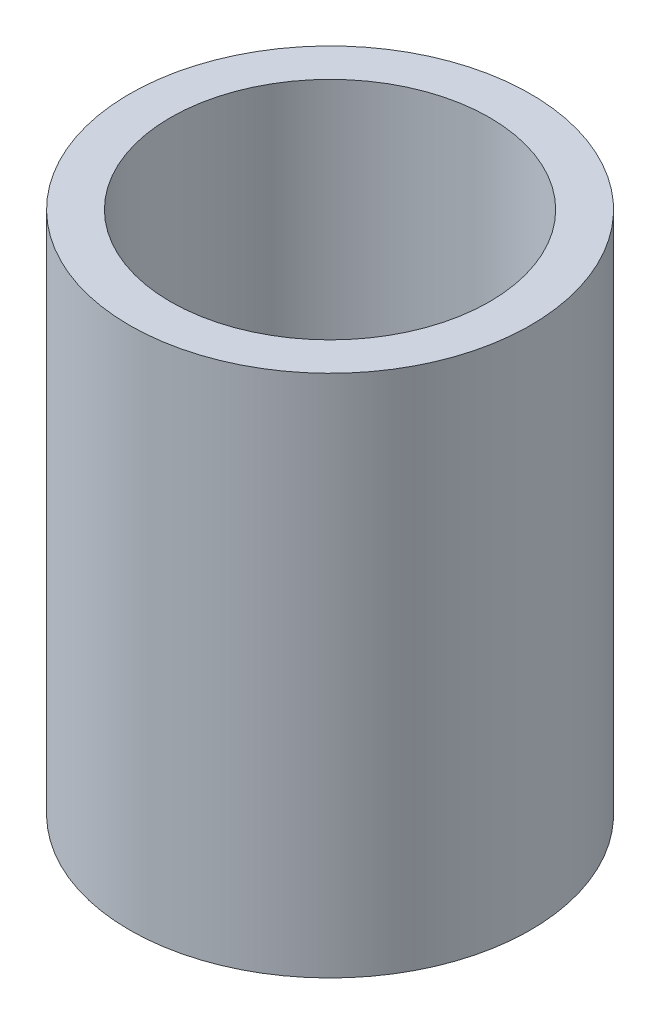
SolidWorks part; units mm, degrees
ref_plane "Front Plane" through (0, 0, 0) normal (0, 0, 1) x (1, 0, 0)
ref_plane "Top Plane" through (0, 0, 0) normal (0, 1, 0) x (1, 0, 0)
ref_plane "Right Plane" through (0, 0, 0) normal (1, 0, 0) x (0, 0, -1)
sketch "Sketch1" plane through (0, 0, 0) normal (0, 1, 0) x (1, 0, 0)
  circle A0 centre (0, 0) radius 24.5
  circle A1 centre (0, 0) radius 19.5
  dimension "D1" = 49
  dimension "D2" = 39
extrude "Boss-Extrude1" add sketch "Sketch1" along normal mid plane 64
